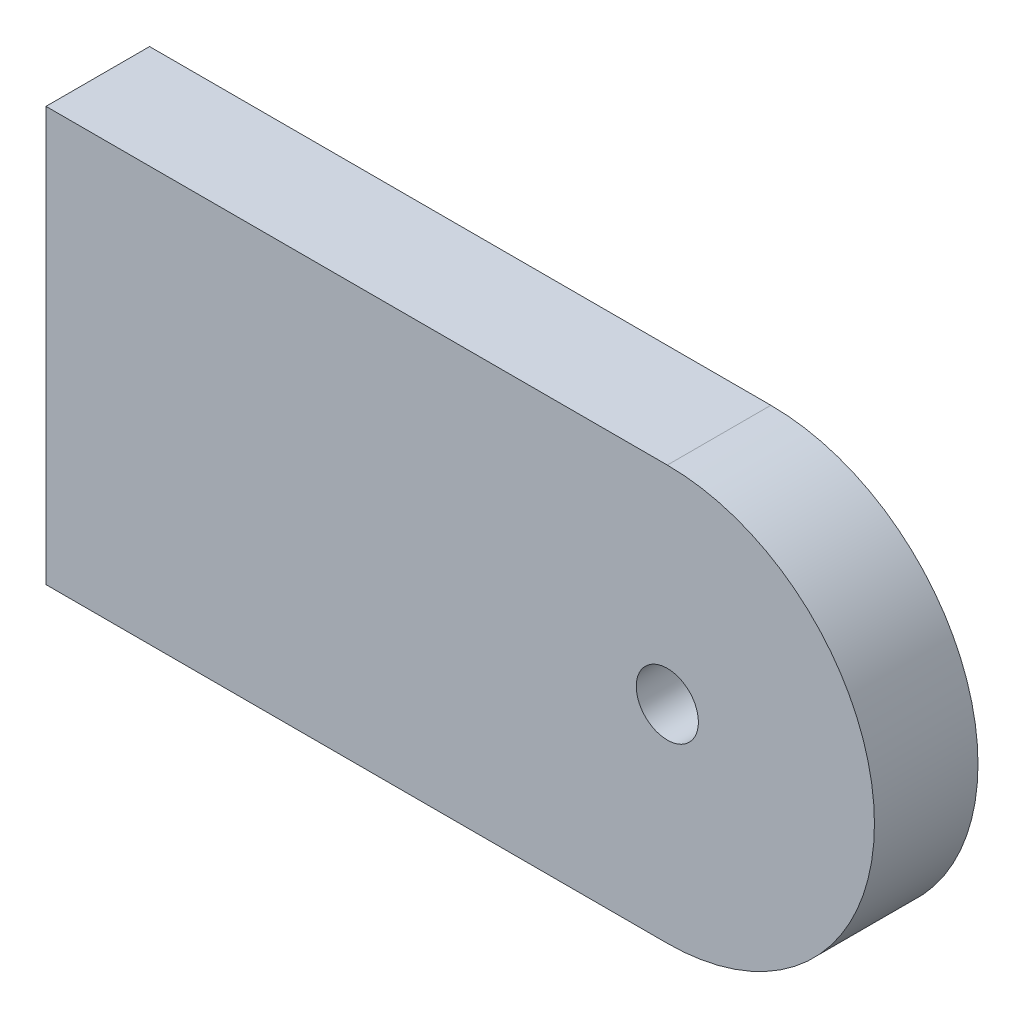
SolidWorks part; units mm, degrees
ref_plane "Front Plane" through (0, 0, 0) normal (0, 0, 1) x (1, 0, 0)
ref_plane "Top Plane" through (0, 0, 0) normal (0, 1, 0) x (1, 0, 0)
ref_plane "Right Plane" through (0, 0, 0) normal (1, 0, 0) x (0, 0, -1)
sketch "Sketch1" plane through (0, 0, 0) normal (0, 0, 1) x (1, 0, 0)
  line L1 (-20, 10) -> (10, 10)
  line L2 (-20, 10) -> (-20, -10)
  line L3 (-20, -10) -> (10, -10)
  line L5 (-20, 10) -> (19.9472, -9.9736) construction
  line L6 (-20, -10) -> (20, 10) construction
  arc A0 (10, -10) -> (10, 10) centre (10, 0) ccw
  circle A1 centre (10, 0) radius 1.5
  point P0 (0, 0)
  point P11 (-20, 0)
  dimension "D1" = 40
  dimension "D3" = 10
  dimension "D4" = 3
  dimension "D2" = 20
extrude "Boss-Extrude1" add sketch "Sketch1" along normal blind 5
